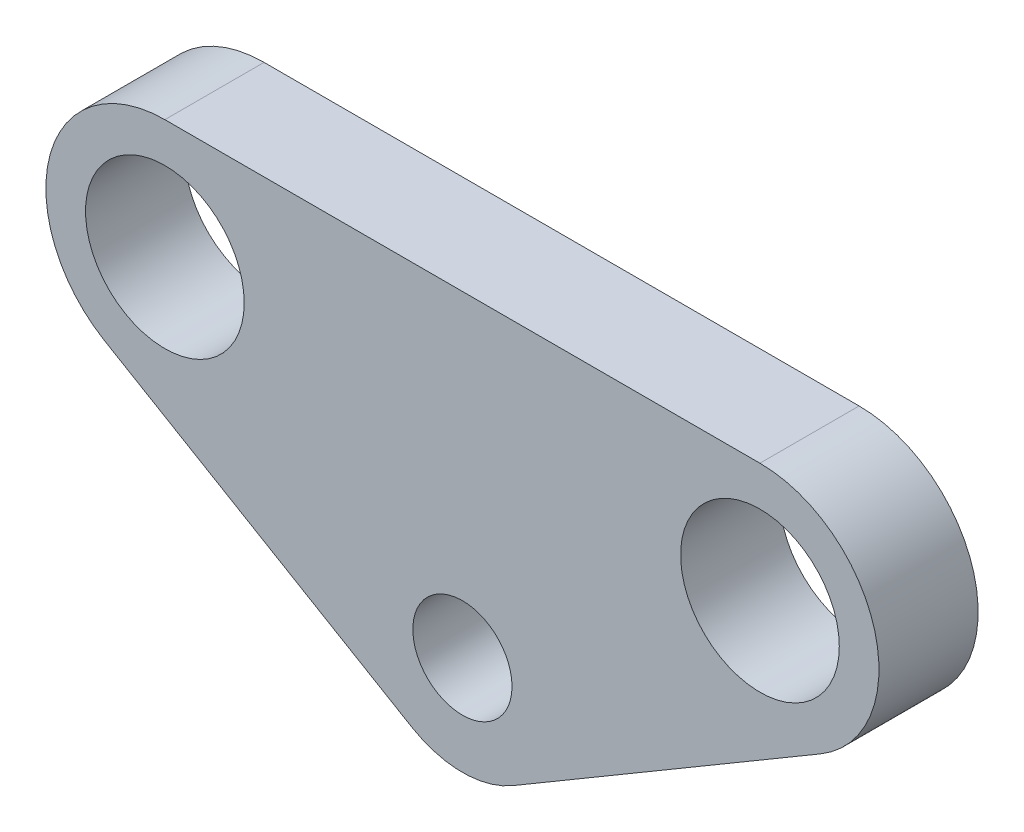
SolidWorks part; units mm, degrees
ref_plane "Front Plane" through (0, 0, 0) normal (0, 0, 1) x (1, 0, 0)
ref_plane "Top Plane" through (0, 0, 0) normal (0, 1, 0) x (1, 0, 0)
ref_plane "Right Plane" through (0, 0, 0) normal (1, 0, 0) x (0, 0, -1)
sketch "Sketch1" plane through (0, 0, 0) normal (0, 0, 1) x (1, 0, 0)
  line L0 (-15, 16) -> (15, 16)
  line L1 (0, 0) -> (0, 18.7938) construction
  line L11 (18.0462, 4.8308) -> (2.5385, -4.3077)
  line L12 (-18.0462, 4.8308) -> (-2.5385, -4.3077)
  circle A0 centre (0, 0) radius 11.5 construction
  circle A1 centre (-15, 10) radius 11.5 construction
  circle A2 centre (15, 10) radius 11.5 construction
  circle A3 centre (-15, 10) radius 4
  arc A5 (-18.0462, 4.8308) -> (-15, 16) centre (-15, 10) cw
  circle A6 centre (15, 10) radius 4
  arc A7 (18.0462, 4.8308) -> (15, 16) centre (15, 10) ccw
  circle A8 centre (0, 0) radius 2.5
  circle A9 centre (0, 0) radius 5 construction
  arc A10 (-2.5385, -4.3077) -> (2.6999, -4.2084) centre (0, 0) ccw
  point P19 (-14.6106, 4.0127)
  point P20 (-3.296, -3.7599)
  point P21 (0, -12)
  dimension "D1" = 23
  dimension "D3" = 8
  dimension "D4" = 6
  dimension "D7" = 10
  dimension "D5" = 5
  dimension "D6" = 10
  dimension "D2" = 15
extrude "Boss-Extrude1" add sketch "Sketch1" along normal blind 5
